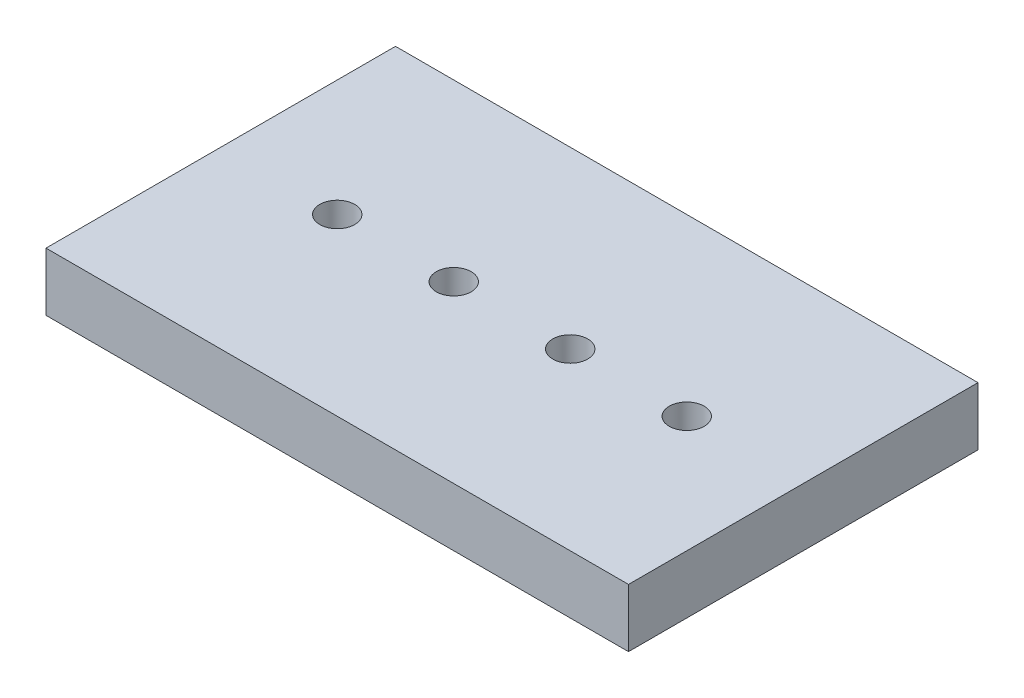
SolidWorks part; units mm, degrees
ref_plane "前视基准面" through (0, 0, 0) normal (0, 0, 1) x (1, 0, 0)
ref_plane "上视基准面" through (0, 0, 0) normal (0, 1, 0) x (1, 0, 0)
ref_plane "右视基准面" through (0, 0, 0) normal (1, 0, 0) x (0, 0, -1)
other "Configuration Table"
sketch "草图1" plane through (0, 0, 0) normal (0, 1, 0) x (1, 0, 0)
  line L1 (-50, -30) -> (50, -30)
  line L2 (-50, -30) -> (-50, 30)
  line L3 (-50, 30) -> (50, 30)
  line L4 (50, -30) -> (50, 30)
  line L5 (-50, -30) -> (50, 30) construction
  line L6 (-50, 30) -> (50, -30) construction
extrude "凸台-拉伸1" add sketch "草图1" along normal blind 10
sketch "草图2" plane through (0, 0, 0) normal (0, 1, 0) x (1, 0, 0)
  circle A0 centre (-30, 0) radius 3
extrude "切除-拉伸1" cut sketch "草图2" along normal blind 20
pattern_linear "阵列(线性)1" count 4 spacing 20 along (1, 0, 0) of "切除-拉伸1"
